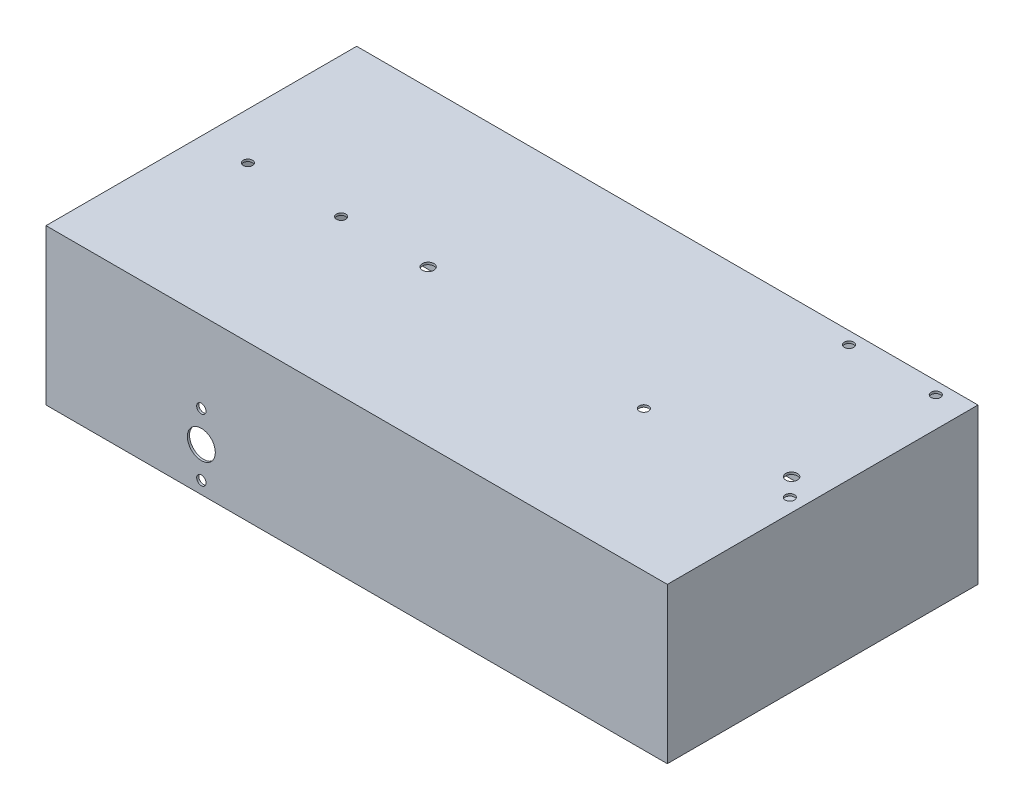
SolidWorks part; units mm, degrees
ref_plane "Front Plane" through (0, 0, 0) normal (0, 0, 1) x (1, 0, 0)
ref_plane "Top Plane" through (0, 0, 0) normal (0, 1, 0) x (1, 0, 0)
ref_plane "Right Plane" through (0, 0, 0) normal (1, 0, 0) x (0, 0, -1)
sketch "Sketch1" plane through (0, 0, 0) normal (0, 1, 0) x (1, 0, 0)
  line L1 (0, 50) -> (200, 50)
  line L2 (0, 50) -> (0, -50)
  line L3 (0, -50) -> (200, -50)
  line L4 (200, 50) -> (200, -50)
  point P4 (0, 0)
  dimension "D1" = 200
  dimension "D2" = 100
extrude "Boss-Extrude1" add sketch "Sketch1" along normal blind 50
sketch "Sketch2" plane through (0, 0, 50) normal (0, 0, 1) x (1, 0, 0)
  line L0 (0, 50) -> (0, 0) construction
  line L1 (50, 24) -> (50, 4) construction
  line L2 (0, 50) -> (200, 50) construction
  circle A0 centre (50, 14) radius 4.5
  circle A1 centre (50, 4) radius 1.5
  circle A2 centre (50, 24) radius 1.5
  point P0 (50, 14)
  point P9 (50, 14)
  dimension "D3" = 9
  dimension "D4" = 3
  dimension "D1" = 50
  dimension "D2" = 36
  dimension "D5" = 20
sketch "Sketch3" plane through (0, 0, 0) normal (0, -1, 0) x (1, 0, 0)
  line L0 (0.7, 49.3) -> (0.7, -49.3)
  line L1 (0.7, -49.3) -> (199.3, -49.3)
  line L2 (199.3, -49.3) -> (199.3, 49.3)
  line L3 (199.3, 49.3) -> (0.7, 49.3)
  line L4 (0, 50) -> (0, -50)
  line L5 (0, -50) -> (200, -50)
  line L6 (200, -50) -> (200, 50)
  line L7 (200, 50) -> (0, 50)
  line L8 (0, 50) -> (0, -50) construction
  line L9 (0, -50) -> (200, -50) construction
  line L10 (200, -50) -> (200, 50) construction
  line L11 (200, 50) -> (0, 50) construction
  dimension "D1" = 0
  dimension "D2" = 0.7
extrude "Cut-Extrude1" cut sketch "Sketch3" against normal offset from surface (49.3 mm away) 0.7 up to face at (100, 50, 0)
sketch "Sketch4" plane through (0, 0, 0) normal (0, -1, 0) x (1, 0, 0)
  line L0 (0.7, -49.3) -> (199.3, -49.3) construction
  line L1 (145, -49.3) -> (199.3, -49.3)
  line L2 (145, -49.3) -> (145, 49.3)
  line L3 (145, 49.3) -> (199.3, 49.3)
  line L4 (199.3, -49.3) -> (199.3, 49.3)
  line L5 (199.3, 49.3) -> (0.7, 49.3) construction
  line L6 (160, -47.9) -> (160, 49.3) construction
  line L7 (200, -50) -> (200, 50) construction
  line L8 (199.3, -49.3) -> (199.3, 49.3) construction
  circle A0 centre (160, 0.7) radius 11.43 construction
  point P12 (160, 0.7)
  dimension "D3" = 22.86
  dimension "D1" = 40
  dimension "D2" = 55
  dimension "D4" = 50
extrude "Boss-Extrude2" add sketch "Sketch4" against normal blind 0.7
extrude "Cut-Extrude2" cut sketch "Sketch2" against normal through all
sketch "Sketch6" plane through (0, 0, 50) normal (0, 0, 1) x (1, 0, 0)
  line L0 (4.6, 50) -> (4.6, 0) construction
  line L1 (0, 50) -> (200, 50) construction
  line L2 (200, 0) -> (0, 0) construction
  line L3 (0, 45) -> (200, 45) construction
  line L4 (0, 50) -> (0, 0) construction
  line L5 (200, 50) -> (200, 0) construction
  line L6 (0, 35) -> (200, 35) construction
  line L7 (54.1, 45) -> (54.1, 35) construction
  line L8 (69.1, 45) -> (69.1, 35) construction
  circle A0 centre (4.6, 45) radius 1.5
  circle A1 centre (4.6, 35) radius 1.5
  circle A2 centre (54.1, 45) radius 1.5
  circle A3 centre (54.1, 35) radius 1.5
  circle A4 centre (69.1, 45) radius 1.5
  circle A5 centre (69.1, 35) radius 1.5
  dimension "D1" = 3
  dimension "D3" = 5
  dimension "D4" = 10
  dimension "D5" = 4.6
  dimension "D6" = 15
  dimension "D7" = 54.1
extrude "Cut-Extrude3" [suppressed] cut sketch "Sketch6" against normal up to surface (0.7 mm away)
sketch "Sketch7" plane through (0, 0, 0) normal (-1, 0, 0) x (0, 0, 1)
  line L0 (42, 50) -> (42, 0) construction
  line L1 (-50, 50) -> (50, 50) construction
  line L2 (-50, 0) -> (50, 0) construction
  circle A0 centre (42, 45) radius 1.5
  circle A1 centre (42, 35) radius 1.5
  dimension "D4" = 3
  dimension "D1" = 8
  dimension "D2" = 5
  dimension "D3" = 10
extrude "Cut-Extrude4" [suppressed] cut sketch "Sketch7" against normal up to surface (0.7 mm away)
sketch "Sketch8" plane through (0, 0, 0) normal (0, -1, 0) x (1, 0, 0)
  line L0 (160, -47.9) -> (160, 49.3) construction
  circle A0 centre (160, 8.45) radius 1.21
  circle A1 centre (160, -7.05) radius 1.21
  dimension "D2" = 2.42
  dimension "D1" = 7.75
  dimension "D3" = 7.75
extrude "Cut-Extrude6" cut sketch "Sketch8" against normal blind 1.8 contours A1 | A0
sketch "Sketch9" plane through (0, 50, 0) normal (0, 1, 0) x (1, 0, 0)
  line L0 (0, 0) -> (200, 0) construction
  line L1 (200, 50) -> (200, -50) construction
  circle A0 centre (15, 0) radius 1.5
  circle A1 centre (45, 0) radius 1.5
  dimension "D1" = 3
  dimension "D2" = 15
  dimension "D3" = 30
sketch "Sketch10" plane through (0, 49.3, 0) normal (0, -1, 0) x (1, 0, 0)
  line L0 (0, 0) -> (200, 0)
  line L1 (200, -50) -> (200, 50) construction
  circle A0 centre (190, 0) radius 1.87
  circle A1 centre (73, 0) radius 1.87
  dimension "D2" = 3.74
  dimension "D1" = 117
  dimension "D3" = 10
extrude "Cut-Extrude8" cut sketch "Sketch10" against normal up to surface (0.7 mm away) contours A0 | A1 up to face at (100, 50, 0)
extrude "Cut-Extrude7" cut sketch "Sketch9" against normal through all
sketch "Sketch11" plane through (143.38, 50, -175.08) normal (0, 1, 0) x (0, 0, 1)
  line L6 (129.04, 19.06) -> (129.04, 47) construction
  circle A0 centre (129.04, 47) radius 1.5
  circle A1 centre (181.11, 52.08) radius 1.5
  circle A2 centre (179.84, 3.82) radius 1.5
  circle A3 centre (129.04, 19.06) radius 1.5
  point P12 (195.08, 54.62)
  dimension "D8" = 3
  dimension "D1" = 13.97
  dimension "D2" = 66.04
  dimension "D3" = 15.24
  dimension "D4" = 2.54
  dimension "D5" = 7.62
  dimension "D6" = 50.8
  dimension "D7" = 35.56
  dimension "D9" = 70
  dimension "D10" = 2
extrude "Cut-Extrude9" cut sketch "Sketch11" against normal up to surface (0.7 mm away) up to face at (15, 49.3, 1.5)
